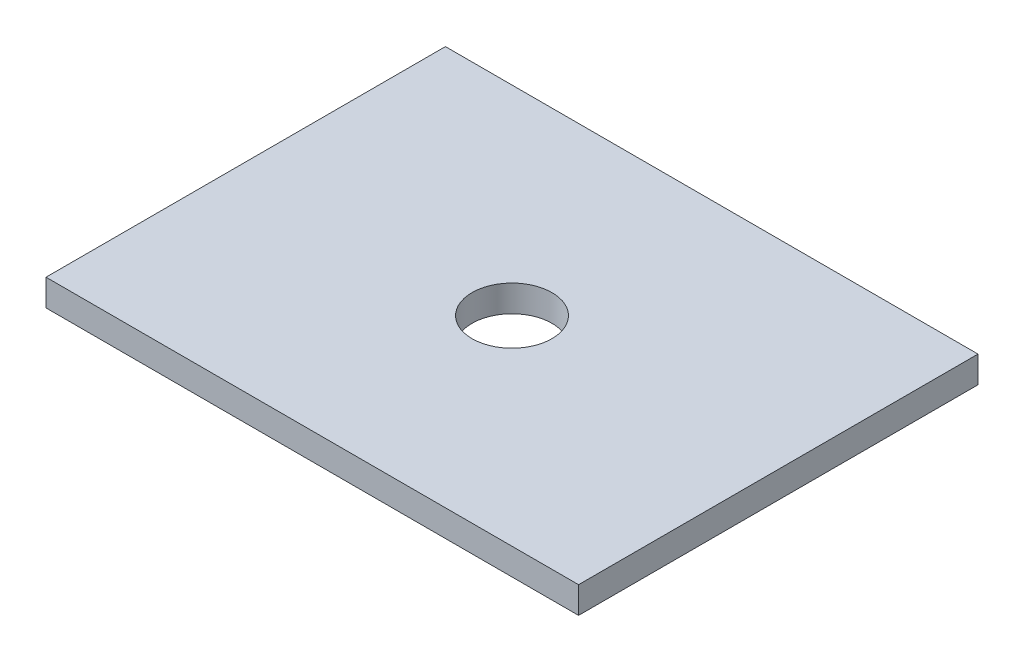
SolidWorks part; units mm, degrees
ref_plane "Front Plane" through (0, 0, 0) normal (0, 0, 1) x (1, 0, 0)
ref_plane "Top Plane" through (0, 0, 0) normal (0, 1, 0) x (1, 0, 0)
ref_plane "Right Plane" through (0, 0, 0) normal (1, 0, 0) x (0, 0, -1)
sketch "Sketch1" plane through (0, 0, 0) normal (0, 1, 0) x (1, 0, 0)
  line L1 (-20, -15) -> (20, -15)
  line L2 (-20, -15) -> (-20, 15)
  line L3 (-20, 15) -> (20, 15)
  line L4 (20, -15) -> (20, 15)
  line L5 (-20, -15) -> (20, 15) construction
  line L6 (-20, 15) -> (20, -15) construction
  point P0 (0, 0)
  dimension "D1" = 40
  dimension "D2" = 30
extrude "Boss-Extrude1" add sketch "Sketch1" along normal blind 2
sketch "Sketch2" plane through (0, 2, 0) normal (0, 1, 0) x (1, 0, 0)
  circle A0 centre (0, 0) radius 3
extrude "Cut-Extrude1" cut sketch "Sketch2" against normal blind 2
